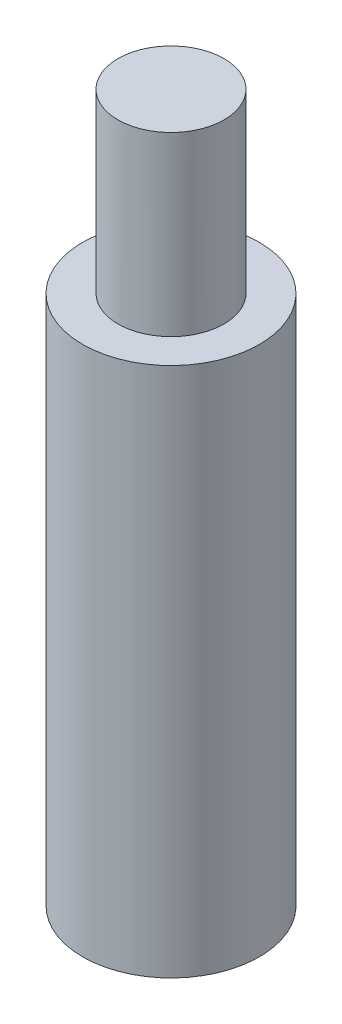
SolidWorks part; units mm, degrees
ref_plane "前视基准面" through (0, 0, 0) normal (0, 0, 1) x (1, 0, 0)
ref_plane "上视基准面" through (0, 0, 0) normal (0, 1, 0) x (1, 0, 0)
ref_plane "右视基准面" through (0, 0, 0) normal (1, 0, 0) x (0, 0, -1)
sketch "草图1" plane through (0, 0, 0) normal (0, 1, 0) x (1, 0, 0)
  circle A0 centre (0, 0) radius 1.5
  dimension "D1" = 3
extrude "凸台-拉伸1" add sketch "草图1" along normal blind 5
sketch "草图2" plane through (0, 0, 0) normal (0, -1, 0) x (1, 0, 0)
  circle A0 centre (0, 0) radius 2.5
  dimension "D1" = 5
extrude "凸台-拉伸2" add sketch "草图2" along normal blind 15
